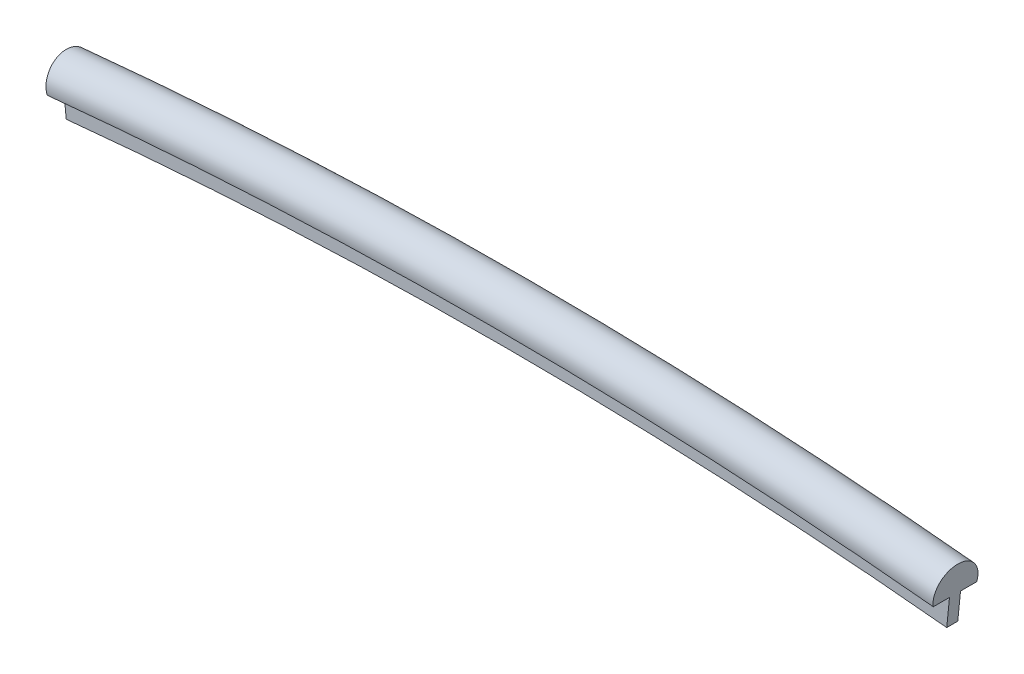
SolidWorks part; units mm, degrees
ref_plane "Front Plane" through (0, 0, 0) normal (0, 0, 1) x (1, 0, 0)
ref_plane "Top Plane" through (0, 0, 0) normal (0, 1, 0) x (1, 0, 0)
ref_plane "Right Plane" through (0, 0, 0) normal (1, 0, 0) x (0, 0, -1)
sketch "Sketch2" plane through (0, 0, 0) normal (1, 0, 0) x (0, 0, -1)
  line L0 (0, 241.3) -> (0, 0) construction
  line L2 (0, 241.3) -> (0, 239.8) construction
  line L3 (0, 239.8) -> (0.3, 239.8)
  line L4 (0, 239.8) -> (-0.3, 239.8)
  line L5 (-0.3, 239.8) -> (-0.3, 241.3)
  line L6 (0.3, 239.8) -> (0.3, 241.3)
  line L7 (0, 241.3) -> (0, 242.8) construction
  line L8 (-1.18, 241.3) -> (-0.3, 241.3)
  line L9 (0.3, 241.3) -> (1.18, 241.3)
  arc A0 (-1.18, 241.3) -> (1.18, 241.3) centre (0, 241.586) cw
  point P14 (0, 241.3)
ref_axis "Axis2" through (0, 0, 70.5976) along (0, 0, -1)
revolve "Revolve1" add sketch "Sketch2" angle 5.718 about axis through (0, 0, 70.5976) along (0, 0, -1)
